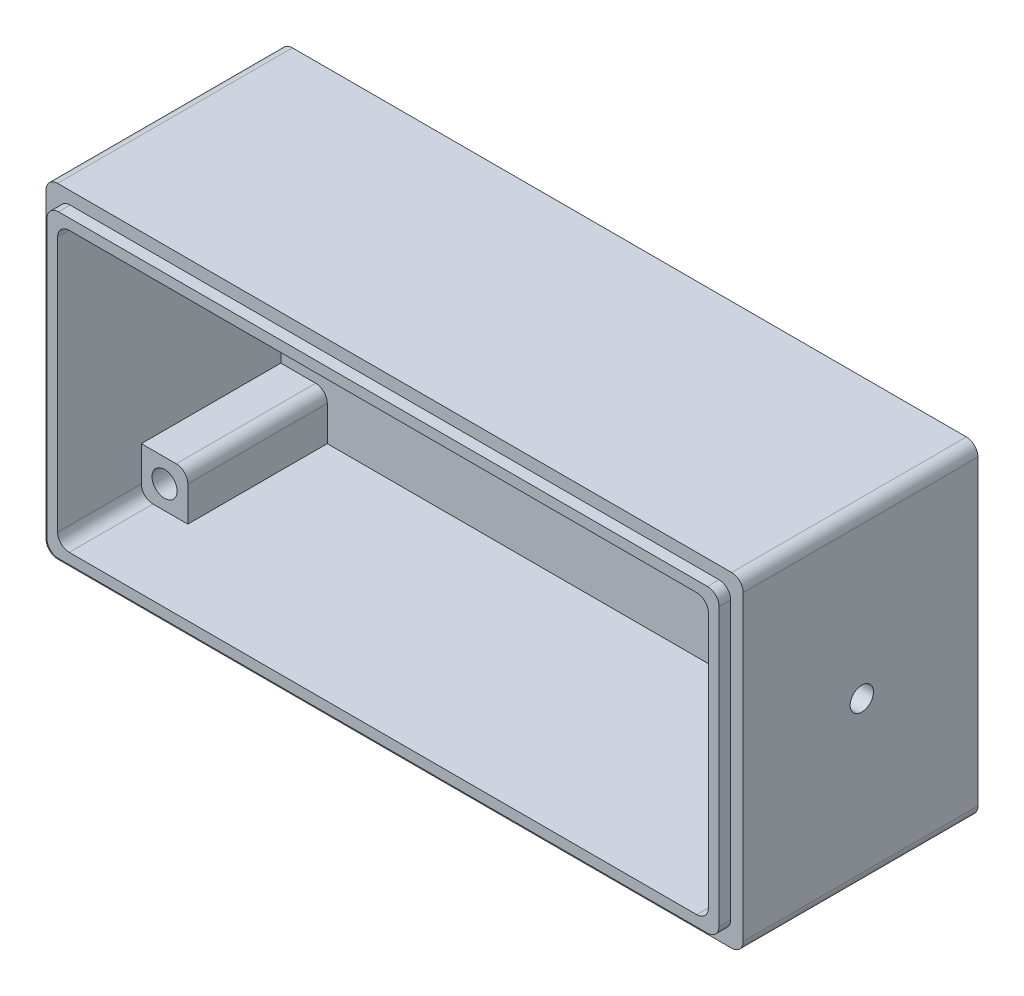
SolidWorks part; units mm, degrees
ref_plane "Front Plane" through (0, 0, 0) normal (0, 0, 1) x (1, 0, 0)
ref_plane "Top Plane" through (0, 0, 0) normal (0, 1, 0) x (1, 0, 0)
ref_plane "Right Plane" through (0, 0, 0) normal (1, 0, 0) x (0, 0, -1)
sketch "Sketch1" plane through (0, 0, 0) normal (0, 0, 1) x (1, 0, 0)
  line L1 (-47.625, -22.225) -> (47.625, -22.225)
  line L2 (-47.625, -22.225) -> (-47.625, 22.225)
  line L3 (-47.625, 22.225) -> (47.625, 22.225)
  line L4 (47.625, -22.225) -> (47.625, 22.225)
  line L5 (-47.625, -22.225) -> (47.625, 22.225) construction
  line L6 (-47.625, 22.225) -> (47.625, -22.225) construction
  point P0 (0, 0)
  dimension "D1" = 44.45
  dimension "D2" = 95.25
extrude "Boss-Extrude1" add sketch "Sketch1" along normal blind 3.175
sketch "Sketch2" plane through (0, 0, 3.175) normal (0, 0, 1) x (1, 0, 0)
  line L1 (-44.45, -19.05) -> (44.45, -19.05)
  line L2 (-44.45, -19.05) -> (-44.45, 19.05)
  line L3 (-44.45, 19.05) -> (44.45, 19.05)
  line L4 (44.45, -19.05) -> (44.45, 19.05)
  line L5 (-44.45, -19.05) -> (44.45, 19.05) construction
  line L6 (-44.45, 19.05) -> (44.45, -19.05) construction
  line L7 (-47.625, -22.225) -> (47.625, -22.225)
  line L8 (-47.625, -22.225) -> (-47.625, 22.225)
  line L9 (-47.625, 22.225) -> (47.625, 22.225)
  line L10 (47.625, -22.225) -> (47.625, 22.225)
  line L11 (-47.625, -22.225) -> (47.625, 22.225) construction
  line L12 (-47.625, 22.225) -> (47.625, -22.225) construction
  point P0 (0, 0)
  point P6 (0, 0)
  dimension "D1" = 3.175
  dimension "D2" = 3.175
extrude "Boss-Extrude2" add sketch "Sketch2" along normal blind 28.9
sketch "Sketch3" plane through (0, 0, 0) normal (0, 0, -1) x (-1, 0, 0)
  line L0 (0, 0) -> (47.625, 0) construction
  line L1 (47.625, 22.225) -> (47.625, -22.225) construction
  line L2 (0, 0) -> (0, 22.225) construction
  line L3 (-47.625, 22.225) -> (47.625, 22.225) construction
  circle A0 centre (27.051, 0) radius 1.7
  dimension "D2" = 3.4
  dimension "D1" = 27.051
extrude "Cut-Extrude1" cut sketch "Sketch3" against normal through all
mirror "Mirror1" about plane through (0, 0, 0) normal (1, 0, 0) of "Cut-Extrude1"
sketch "Sketch4" plane through (0, 0, 0) normal (0, 0, -1) x (-1, 0, 0)
  line L1 (30.4978, 0) -> (28.7744, 2.985)
  line L2 (28.7744, 2.985) -> (25.3276, 2.985)
  line L3 (25.3276, 2.985) -> (23.6042, 0)
  line L4 (23.6042, 0) -> (25.3276, -2.985)
  line L5 (25.3276, -2.985) -> (28.7744, -2.985)
  line L6 (28.7744, -2.985) -> (30.4978, 0)
  circle A0 centre (27.051, 0) radius 2.985 construction
  dimension "D1" = 5.97
extrude "Cut-Extrude2" cut sketch "Sketch4" against normal blind 1.7145
mirror "Mirror2" about plane through (0, 0, 0) normal (1, 0, 0) of "Cut-Extrude2"
fillet "Fillet1" radius 1.5875 8 edges at (-47.625, 22.225, 16.0375) (47.625, 22.225, 16.0375) (47.625, -22.225, 16.0375) (-47.625, -22.225, 16.0375) (44.45, 19.05, 17.625) (44.45, -19.05, 17.625) (-44.45, -19.05, 17.625) (-44.45, 19.05, 17.625)
sketch "Sketch5" plane through (0, 0, 32.075) normal (0, 0, 1) x (1, 0, 0)
  line L0 (44.45, -17.4625) -> (44.45, 17.4625) construction
  line L1 (-44.323, -20.5105) -> (44.323, -20.5105)
  line L2 (-45.9105, -18.923) -> (-45.9105, 18.923)
  line L3 (-44.323, 20.5105) -> (44.323, 20.5105)
  line L4 (45.9105, -18.923) -> (45.9105, 18.923)
  line L5 (-45.9105, -20.5105) -> (45.9105, 20.5105) construction
  line L6 (-45.9105, 20.5105) -> (45.9105, -20.5105) construction
  line L7 (42.8625, 19.05) -> (-42.8625, 19.05) construction
  line L8 (-42.8625, -19.05) -> (42.8625, -19.05) construction
  line L9 (42.8625, 19.05) -> (-42.8625, 19.05) construction
  line L10 (-44.45, 17.4625) -> (-44.45, -17.4625) construction
  line L11 (44.45, -17.4625) -> (44.45, 17.4625)
  line L12 (-42.8625, -19.05) -> (42.8625, -19.05)
  line L13 (42.8625, 19.05) -> (-42.8625, 19.05)
  line L14 (-44.45, 17.4625) -> (-44.45, -17.4625)
  arc A0 (44.323, 20.5105) -> (45.9105, 18.923) centre (44.323, 18.923) cw
  arc A1 (44.323, -20.5105) -> (45.9105, -18.923) centre (44.323, -18.923) ccw
  arc A2 (-44.323, -20.5105) -> (-45.9105, -18.923) centre (-44.323, -18.923) cw
  arc A3 (-45.9105, 18.923) -> (-44.323, 20.5105) centre (-44.323, 18.923) cw
  arc A4 (44.45, 17.4625) -> (42.8625, 19.05) centre (42.8625, 17.4625) ccw construction
  arc A5 (42.8625, -19.05) -> (44.45, -17.4625) centre (42.8625, -17.4625) ccw construction
  arc A6 (-44.45, -17.4625) -> (-42.8625, -19.05) centre (-42.8625, -17.4625) ccw construction
  arc A7 (-42.8625, 19.05) -> (-44.45, 17.4625) centre (-42.8625, 17.4625) ccw construction
  arc A8 (44.45, 17.4625) -> (42.8625, 19.05) centre (42.8625, 17.4625) ccw
  arc A9 (42.8625, -19.05) -> (44.45, -17.4625) centre (42.8625, -17.4625) ccw
  arc A10 (-44.45, -17.4625) -> (-42.8625, -19.05) centre (-42.8625, -17.4625) ccw
  arc A11 (-42.8625, 19.05) -> (-44.45, 17.4625) centre (-42.8625, 17.4625) ccw
  point P0 (0, 0)
  dimension "D3" = 1.5875
  dimension "D1" = 1.4605
  dimension "D2" = 1.4605
extrude "Boss-Extrude3" add sketch "Sketch5" along normal blind 1.5875
sketch "Sketch6" plane through (0, 0, 3.175) normal (0, 0, 1) x (1, 0, 0)
  line L0 (-44.45, 17.4625) -> (-44.45, -17.4625) construction
  line L1 (-44.45, 19.05) -> (-38.1, 19.05)
  line L2 (-44.45, 19.05) -> (-44.45, 12.7)
  line L3 (-44.45, 12.7) -> (-39.6875, 12.7)
  line L4 (-38.1, 19.05) -> (-38.1, 14.2875)
  line L5 (42.8625, 19.05) -> (-42.8625, 19.05) construction
  line L6 (-41.275, 19.05) -> (-41.275, 12.7) construction
  line L7 (-44.45, 15.875) -> (-38.1, 15.875) construction
  arc A0 (-39.6875, 12.7) -> (-38.1, 14.2875) centre (-39.6875, 14.2875) ccw
  circle A1 centre (-41.275, 15.875) radius 1.715
  point P11 (-38.1, 12.7)
  dimension "D3" = 1.5875
  dimension "D4" = 3.43
  dimension "D1" = 6.35
  dimension "D2" = 6.35
extrude "Boss-Extrude4" add sketch "Sketch6" along normal blind 19.05
sketch "Sketch7" plane through (0, 0, 22.225) normal (0, 0, 1) x (1, 0, 0)
  circle A0 centre (-41.275, 15.875) radius 1.715 construction
  circle A1 centre (-41.275, 15.875) radius 1.715
extrude "Cut-Extrude3" cut sketch "Sketch7" against normal through all
sketch "Sketch8" plane through (0, 0, 0) normal (0, 0, -1) x (-1, 0, 0)
  line L1 (37.8282, 15.875) -> (39.5516, 12.89)
  line L2 (39.5516, 12.89) -> (42.9984, 12.89)
  line L3 (42.9984, 12.89) -> (44.7218, 15.875)
  line L4 (44.7218, 15.875) -> (42.9984, 18.86)
  line L5 (42.9984, 18.86) -> (39.5516, 18.86)
  line L6 (39.5516, 18.86) -> (37.8282, 15.875)
  circle A0 centre (41.275, 15.875) radius 2.985 construction
  dimension "D1" = 5.97
extrude "Cut-Extrude4" cut sketch "Sketch8" against normal blind 1.7145
mirror "Mirror3" about plane through (0, 0, 0) normal (1, 0, 0) of "Boss-Extrude4", "Cut-Extrude3", "Cut-Extrude4" second plane through (0, 0, 0) second plane normal (0, 1, 0)
sketch "Sketch9" plane through (44.45, 0, 0) normal (-1, 0, 0) x (0, 0, 1)
  line L0 (3.175, -12.7) -> (3.175, 12.7) construction
  circle A0 centre (15.875, 0) radius 1.59
  dimension "D1" = 3.18
  dimension "D2" = 12.7
extrude "Cut-Extrude5" cut sketch "Sketch9" against normal through all
